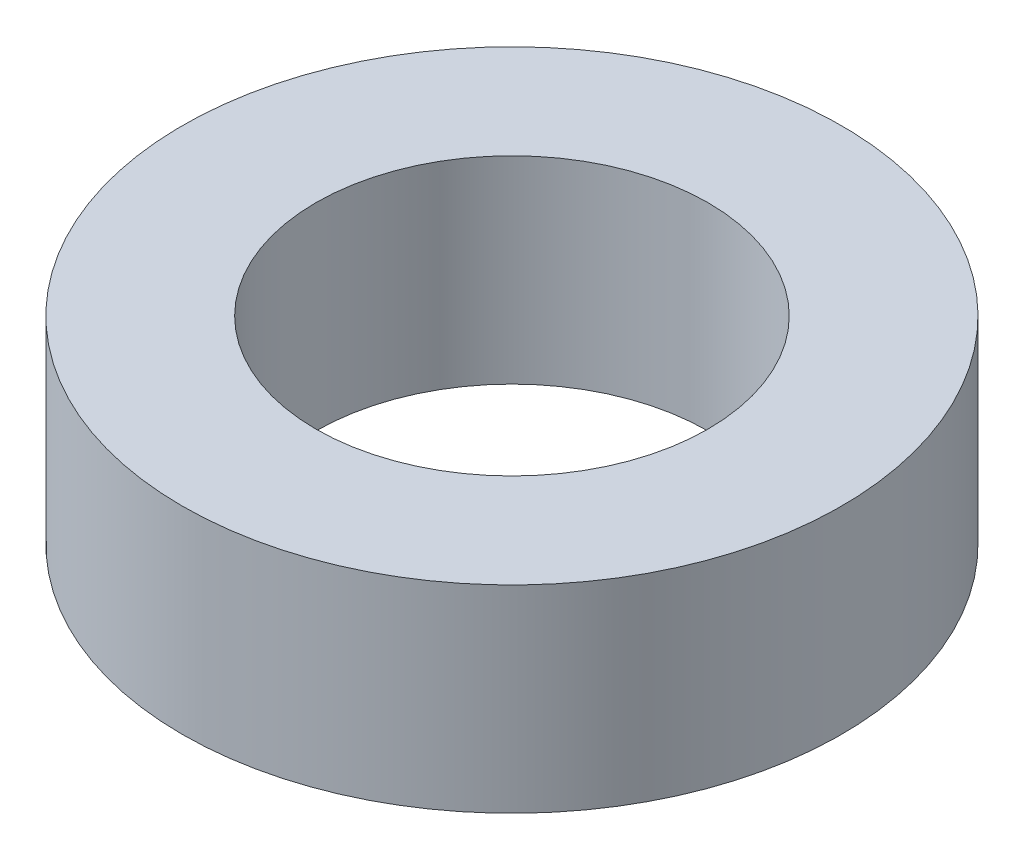
SolidWorks part; units mm, degrees
ref_plane "Front Plane" through (0, 0, 0) normal (0, 0, 1) x (1, 0, 0)
ref_plane "Top Plane" through (0, 0, 0) normal (0, 1, 0) x (1, 0, 0)
ref_plane "Right Plane" through (0, 0, 0) normal (1, 0, 0) x (0, 0, -1)
sketch "Sketch1" plane through (0, 0, 0) normal (1, 0, 0) x (0, 0, -1)
  line L0 (0, 16.2573) -> (0, -12.4561) construction
  line L1 (-10, 3) -> (-10, -3)
  line L2 (-10, -3) -> (-5.95, -3)
  line L3 (-5.95, -3) -> (-5.95, 3)
  line L4 (-5.95, 3) -> (-10, 3)
  point P5 (-10, 0)
  dimension "D1" = 20
  dimension "D2" = 11.9
  dimension "D3" = 6
  dimension "D4" = 4.05
revolve "Revolve1" add sketch "Sketch1" angle 360 about L0
